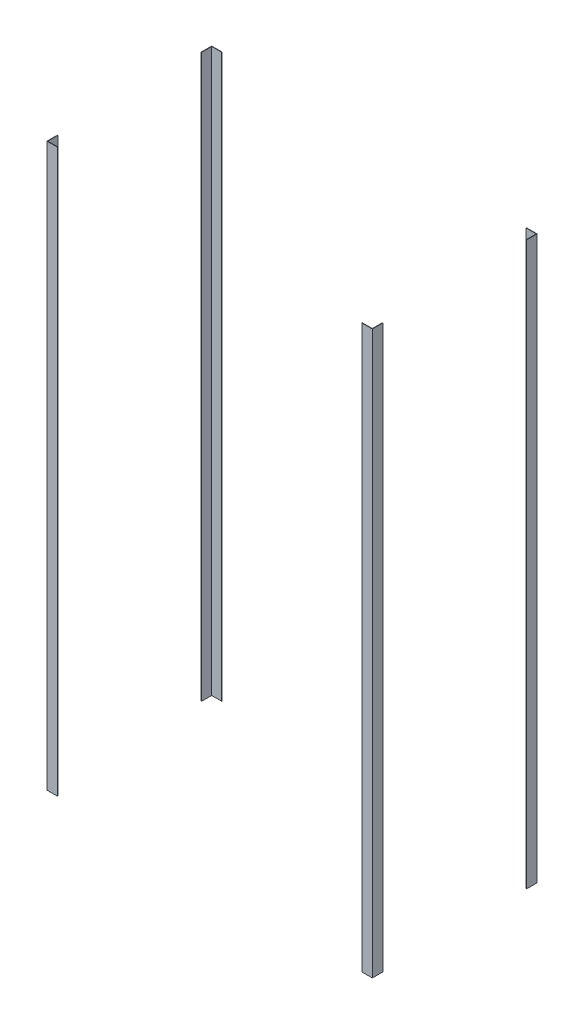
SolidWorks part; units mm, degrees
material "Plain Carbon Steel"
ref_plane "Front Plane" through (0, 0, 0) normal (0, 0, 1) x (1, 0, 0)
ref_plane "Top Plane" through (0, 0, 0) normal (0, 1, 0) x (1, 0, 0)
ref_plane "Right Plane" through (0, 0, 0) normal (1, 0, 0) x (0, 0, -1)
sketch "Sketch1" plane through (0, 0, 0) normal (0, 1, 0) x (1, 0, 0)
  line L1 (-617.5375, -312.7375) -> (-577.85, -312.7375)
  line L2 (-617.5375, -312.7375) -> (-617.5375, -273.05)
  line L3 (-617.5375, 312.7375) -> (-577.85, 312.7375)
  line L4 (617.5375, -312.7375) -> (617.5375, -273.05)
  line L5 (-617.5375, -312.7375) -> (617.5375, 312.7375) construction
  line L6 (-617.5375, 312.7375) -> (617.5375, -312.7375) construction
  line L10 (-615.95, -311.15) -> (-615.95, -273.05)
  line L11 (-615.95, 311.15) -> (-577.85, 311.15)
  line L12 (615.95, -311.15) -> (615.95, -273.05)
  line L13 (-615.95, -311.15) -> (-577.85, -311.15)
  line L14 (-577.85, 312.7375) -> (-577.85, 311.15)
  line L15 (577.85, 312.7375) -> (577.85, 311.15)
  line L16 (-617.5375, 273.05) -> (-615.95, 273.05)
  line L17 (-617.5375, -273.05) -> (-615.95, -273.05)
  line L18 (615.95, 273.05) -> (617.5375, 273.05)
  line L19 (615.95, -273.05) -> (617.5375, -273.05)
  line L20 (-577.85, -311.15) -> (-577.85, -312.7375)
  line L21 (577.85, -311.15) -> (577.85, -312.7375)
  line L22 (577.85, 312.7375) -> (617.5375, 312.7375)
  line L23 (577.85, 311.15) -> (615.95, 311.15)
  line L24 (-577.85, 312.7375) -> (577.85, 312.7375) construction
  line L25 (-617.5375, 312.7375) -> (617.5375, 312.7375) construction
  line L26 (577.85, -312.7375) -> (617.5375, -312.7375)
  line L27 (-577.85, 311.15) -> (577.85, 311.15) construction
  line L28 (-615.95, 311.15) -> (615.95, 311.15) construction
  line L29 (577.85, -311.15) -> (615.95, -311.15)
  line L30 (-577.85, -312.7375) -> (577.85, -312.7375) construction
  line L31 (-617.5375, -312.7375) -> (617.5375, -312.7375) construction
  line L32 (617.5375, 273.05) -> (617.5375, 312.7375)
  line L33 (-577.85, -311.15) -> (577.85, -311.15) construction
  line L34 (-615.95, -311.15) -> (615.95, -311.15) construction
  line L35 (615.95, 273.05) -> (615.95, 311.15)
  line L36 (617.5375, -273.05) -> (617.5375, 273.05) construction
  line L37 (617.5375, -312.7375) -> (617.5375, 312.7375) construction
  line L38 (-617.5375, 273.05) -> (-617.5375, 312.7375)
  line L39 (615.95, -273.05) -> (615.95, 273.05) construction
  line L40 (615.95, -311.15) -> (615.95, 311.15) construction
  line L41 (-615.95, 273.05) -> (-615.95, 311.15)
  line L42 (-617.5375, -273.05) -> (-617.5375, 273.05) construction
  line L43 (-617.5375, -312.7375) -> (-617.5375, 312.7375) construction
  line L45 (-615.95, -273.05) -> (-615.95, 273.05) construction
  line L46 (-615.95, -311.15) -> (-615.95, 311.15) construction
  point P0 (0, 0)
  dimension "D1" = 1235.075
  dimension "D2" = 625.475
  dimension "D4" = 38.1
  dimension "D3" = 1.5875
extrude "Boss-Extrude1" add sketch "Sketch1" along normal blind 2133.6
